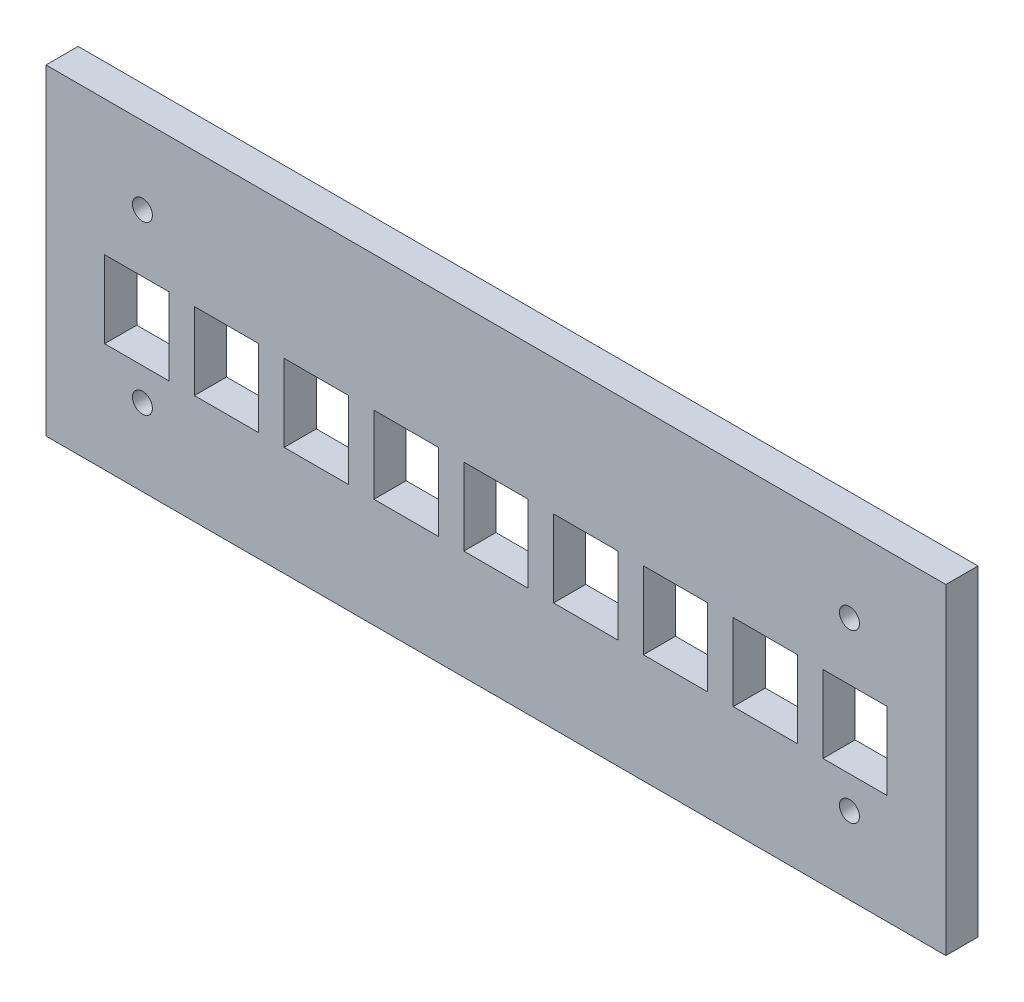
SolidWorks part; units mm, degrees
ref_plane "Plan de face" through (0, 0, 0) normal (0, 0, 1) x (1, 0, 0)
ref_plane "Plan de dessus" through (0, 0, 0) normal (0, 1, 0) x (1, 0, 0)
ref_plane "Plan de droite" through (0, 0, 0) normal (1, 0, 0) x (0, 0, -1)
sketch "Esquisse1" plane through (0, 0, 0) normal (0, 0, 1) x (1, 0, 0)
  line L0 (8.97, -8) -> (8.97, 4)
  line L5 (-70, -25) -> (70, -25)
  line L6 (-70, -25) -> (-70, 25)
  line L7 (-70, 25) -> (70, 25)
  line L8 (70, -25) -> (70, 25)
  line L9 (-70, -25) -> (70, 25) construction
  line L10 (-70, 25) -> (70, -25) construction
  line L11 (-5, -8) -> (5, -8)
  line L12 (-5, -8) -> (-5, 4)
  line L13 (-5, 4) -> (5, 4)
  line L14 (5, -8) -> (5, 4)
  line L15 (-5, -8) -> (5, 4) construction
  line L16 (-5, 4) -> (5, -8) construction
  line L17 (8.97, -8) -> (18.97, -8)
  line L18 (18.97, -8) -> (18.97, 4)
  line L19 (8.97, 4) -> (18.97, 4)
  line L20 (22.94, -8) -> (22.94, 4)
  line L21 (22.94, -8) -> (32.94, -8)
  line L22 (32.94, -8) -> (32.94, 4)
  line L23 (22.94, 4) -> (32.94, 4)
  line L24 (36.91, -8) -> (36.91, 4)
  line L25 (36.91, -8) -> (46.91, -8)
  line L26 (46.91, -8) -> (46.91, 4)
  line L27 (36.91, 4) -> (46.91, 4)
  line L28 (50.88, -8) -> (50.88, 4)
  line L29 (50.88, -8) -> (60.88, -8)
  line L30 (60.88, -8) -> (60.88, 4)
  line L31 (50.88, 4) -> (60.88, 4)
  line L32 (-5, -8) -> (8.97, -8) construction
  line L33 (-18.97, -8) -> (-18.97, 4)
  line L34 (-18.97, -8) -> (-8.97, -8)
  line L35 (-8.97, -8) -> (-8.97, 4)
  line L36 (-18.97, 4) -> (-8.97, 4)
  line L37 (-32.94, -8) -> (-32.94, 4)
  line L38 (-32.94, -8) -> (-22.94, -8)
  line L39 (-22.94, -8) -> (-22.94, 4)
  line L40 (-32.94, 4) -> (-22.94, 4)
  line L41 (-46.91, -8) -> (-46.91, 4)
  line L42 (-46.91, -8) -> (-36.91, -8)
  line L43 (-36.91, -8) -> (-36.91, 4)
  line L44 (-46.91, 4) -> (-36.91, 4)
  line L45 (-60.88, -8) -> (-60.88, 4)
  line L46 (-60.88, -8) -> (-50.88, -8)
  line L47 (-50.88, -8) -> (-50.88, 4)
  line L48 (-60.88, 4) -> (-50.88, 4)
  line L49 (-5, -8) -> (-18.97, -8) construction
  line L50 (0, 0) -> (0, 7.7631) construction
  line L51 (0, 0) -> (6.8675, 0) construction
  line L52 (0, -2) -> (0, 0) construction
  circle A0 centre (-55, -13) radius 1.55
  circle A1 centre (-55, 13) radius 1.55
  circle A2 centre (55, -13) radius 1.55
  circle A3 centre (55, 13) radius 1.55
  point P0 (0, 0)
  point P5 (0, 7.7631)
  point P8 (6.8675, 0)
  dimension "D9" = 3.1
  dimension "D1" = 140
  dimension "D2" = 50
  dimension "D3" = 10
  dimension "D4" = 12
  dimension "D6" = 13.97
  dimension "D8" = 13.97
  dimension "D10" = 15
  dimension "D11" = 12
  dimension "D12" = 23
  dimension "D5" = 5
  dimension "D7" = 5
extrude "Boss.-Extru.1" add sketch "Esquisse1" against normal blind 5
